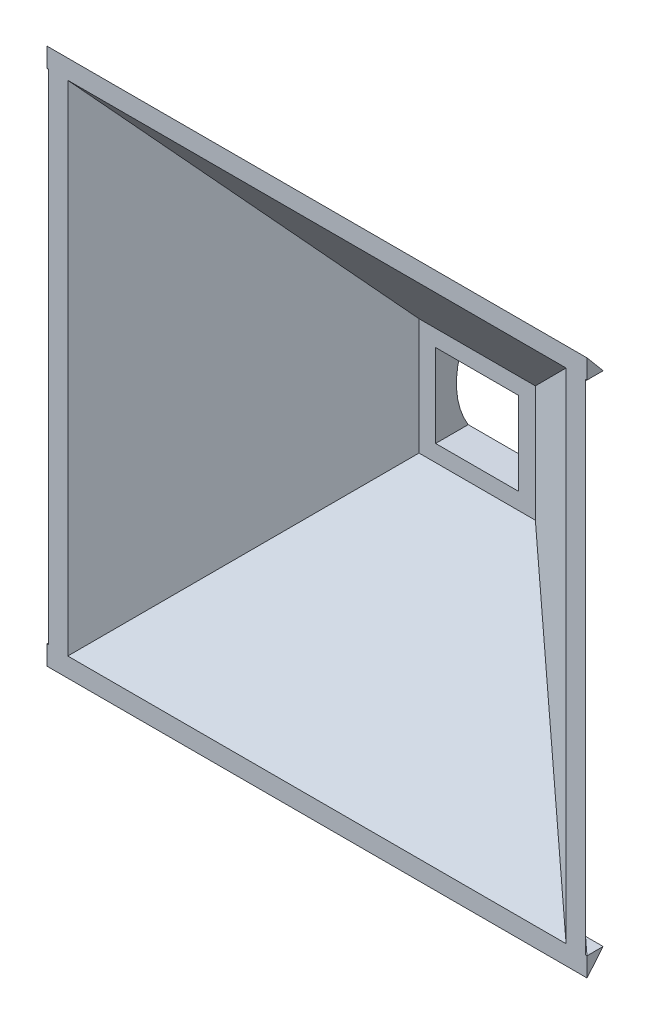
SolidWorks part; units mm, degrees
ref_plane "Front Plane" through (0, 0, 0) normal (0, 0, 1) x (1, 0, 0)
ref_plane "Top Plane" through (0, 0, 0) normal (0, 1, 0) x (1, 0, 0)
ref_plane "Right Plane" through (0, 0, 0) normal (1, 0, 0) x (0, 0, -1)
sketch "Sketch1" plane through (0, 0, 0) normal (0, 0, 1) x (1, 0, 0)
  line L0 (-7, 7) -> (-7, -7)
  line L1 (-5, 5) -> (5, 5)
  line L2 (-5, 5) -> (-5, -5)
  line L3 (-5, -5) -> (5, -5)
  line L4 (5, 5) -> (5, -5)
  line L5 (-5, 5) -> (5, -5) construction
  line L6 (-5, -5) -> (5, 5) construction
  line L7 (-7, -7) -> (7, -7)
  line L8 (7, 7) -> (7, -7)
  line L9 (-7, 7) -> (7, 7)
  point P0 (0, 0)
  dimension "D1" = 10
  dimension "D2" = 10
extrude "Boss-Extrude1" add sketch "Sketch1" along normal blind 12
sketch "Sketch2" plane through (7, 0, 0) normal (1, 0, 0) x (0, 0, -1)
  circle A0 centre (0, 0) radius 9.5
  dimension "D1" = 19
extrude "Cut-Extrude1" cut sketch "Sketch2" against normal blind 30
sketch "Sketch4" plane through (0, 0, 0) normal (0, 1, 0) x (1, 0, 0)
  line L0 (-7, -12) -> (-29.9813, -31.2836)
  line L1 (0, -3.0676) -> (0, 3.0676) construction
  line L3 (-7, -12) -> (-7, -6.4226) construction
  line L4 (-7, -10.0595) -> (-32.294, -31.2836)
  line L5 (-7, -10.0595) -> (-7, -12)
  line L6 (-32.294, -31.2836) -> (-29.9813, -31.2836)
  line L7 (7, -10.0595) -> (7, -12)
  line L8 (32.294, -31.2836) -> (29.9813, -31.2836)
  line L9 (7, -12) -> (29.9813, -31.2836)
  line L10 (7, -10.0595) -> (32.294, -31.2836)
  dimension "D1" = 30
  dimension "D4" = 130
extrude "Boss-Extrude2" add sketch "Sketch4" along normal mid plane 60
sketch "Sketch6" plane through (0, 0, 0) normal (1, 0, 0) x (0, 0, -1)
  line L0 (-10.0595, -7) -> (-12, -7)
  line L1 (-31.2836, -30) -> (-29.3431, -30)
  line L2 (-31.2836, -30) -> (-10.0595, -30) construction
  line L3 (-29.3431, -30) -> (-10.0595, -7)
  line L4 (-12, -7) -> (-31.2836, -30)
  line L5 (13.6736, 0) -> (-13.6736, 0) construction
  line L6 (-31.2836, 30) -> (-29.3431, 30)
  line L7 (-10.0595, 7) -> (-12, 7)
  line L8 (-12, 7) -> (-31.2836, 30)
  line L9 (-29.3431, 30) -> (-10.0595, 7)
extrude "Boss-Extrude3" add sketch "Sketch6" along normal mid plane 65
sketch "Sketch7" plane through (32.5, 0, 0) normal (1, 0, 0) x (0, 0, -1)
  line L0 (-29.3431, 30) -> (-10.0595, 7)
  line L1 (-10.0595, 7) -> (-10.0595, 30)
  line L2 (-10.0595, 30) -> (-29.3431, 30)
  line L3 (13.6736, 0) -> (-13.6736, 0) construction
  line L4 (-29.3431, -30) -> (-10.0595, -7)
  line L5 (-10.0595, -7) -> (-10.0595, -30)
  line L6 (-10.0595, -30) -> (-29.3431, -30)
extrude "Cut-Extrude2" cut sketch "Sketch7" against normal through all
sketch "Sketch9" plane through (0, 0, 0) normal (0, 1, 0) x (1, 0, 0)
  line L0 (-32.5, -31.2836) -> (-7, -10.0595)
  line L1 (-7, -10.0595) -> (-32.5, -10.0595)
  line L2 (-32.5, -10.0595) -> (-32.5, -31.2836)
  line L3 (0, -13.6736) -> (0, 13.6736) construction
  line L4 (7, -10.0595) -> (32.5, -10.0595)
  line L5 (32.5, -31.2836) -> (7, -10.0595)
  line L6 (32.5, -10.0595) -> (32.5, -31.2836)
extrude "Cut-Extrude3" cut sketch "Sketch9" against normal mid plane 65
sketch "Sketch10" plane through (0, 0, 0) normal (1, 0, 0) x (0, 0, -1)
  line L0 (-31.2836, -30) -> (-29.3431, -30)
  line L1 (-29.3431, -30) -> (-31.2836, -32.3145)
  line L2 (-31.2836, -32.3145) -> (-31.2836, -30)
  line L3 (-10.0595, -7) -> (-29.3431, -30) construction
  line L4 (13.6736, 0) -> (-13.6736, 0) construction
  line L5 (-29.3431, 30) -> (-31.2836, 32.3145)
  line L6 (-31.2836, 30) -> (-29.3431, 30)
  line L7 (-31.2836, 32.3145) -> (-31.2836, 30)
  dimension "D1" = 180
extrude "Boss-Extrude4" add sketch "Sketch10" along normal mid plane 65
